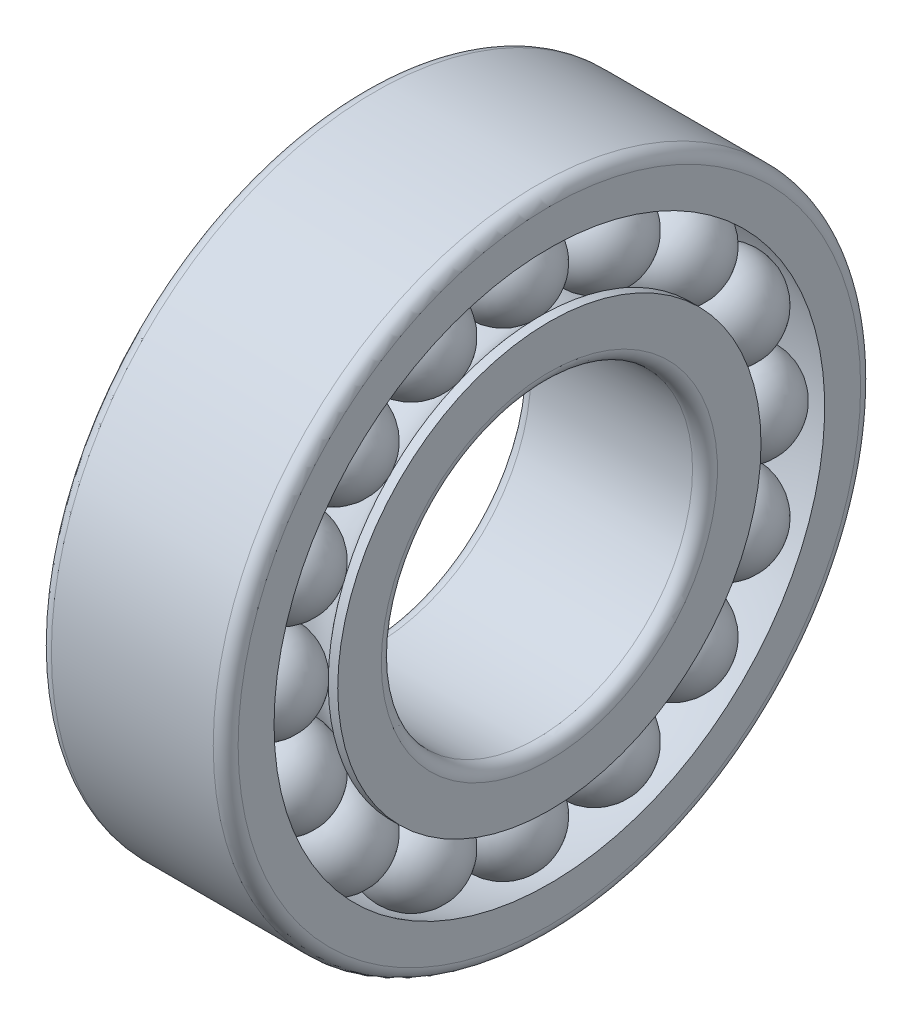
SolidWorks part; units mm, degrees
ref_plane "Front" through (0, 0, 0) normal (0, 0, 1) x (1, 0, 0)
ref_plane "Top" through (0, 0, 0) normal (0, 1, 0) x (1, 0, 0)
ref_plane "Right" through (0, 0, 0) normal (1, 0, 0) x (0, 0, -1)
sketch "Sketch1" plane through (0, 0, 0) normal (0, 0, 1) x (1, 0, 0)
  line L0 (0, 0) -> (10.4156, 0) construction
  line L1 (-7.5, 12.5) -> (7.5, 12.5)
  line L2 (7.5, 12.5) -> (7.5, 17)
  line L3 (7.5, 17) -> (6.7375, 17)
  line L4 (-7.5, 17) -> (-7.5, 12.5)
  line L5 (-6.7375, 17) -> (-7.5, 17)
  line L6 (0.7625, 17) -> (-0.7625, 17)
  circle A0 centre (-3.75, 19.25) radius 3.74 construction
  circle A1 centre (3.75, 19.25) radius 3.74 construction
  arc A2 (-6.7375, 17) -> (-0.7625, 17) centre (-3.75, 19.25) ccw
  arc A3 (0.7625, 17) -> (6.7375, 17) centre (3.75, 19.25) ccw
  point P8 (0, 12.5)
  dimension "QXD" = 7.48
  dimension "XD1" = 34
  dimension "XD" = 25
  dimension "DB" = 15
  dimension "QDD" = 38.5
  dimension "D1" = 3.75
  dimension "D2" = 3.75
revolve "Revovle1" add sketch "Sketch1" angle 360 about L0
sketch "Sketch2" plane through (0, 0, 0) normal (0, 0, 1) x (1, 0, 0)
  line L0 (-7.4995, 19.25) -> (-0.0005, 19.25)
  line L1 (-4.0336, 19.25) -> (6.5093, 19.25) construction
  arc A2 (-7.4995, 19.25) -> (-0.0005, 19.25) centre (-3.75, 19.25) ccw
  dimension "D2" = 3.75
  dimension "D1" = 19.25
  dimension "QXD" = 7.499
revolve "Revolve2" add sketch "Sketch2" angle 360 about L1
mirror "Mirror1" about plane through (0, 0, 0) normal (1, 0, 0) of "Revolve2"
sketch "Sketch3" plane through (0, 0, 0) normal (0, 0, 1) x (1, 0, 0)
  line L0 (-7.5, 22.1147) -> (-7.5, 26)
  line L1 (-7.5, 26) -> (7.5, 26)
  line L2 (7.5, 26) -> (7.5, 22.1147)
  line L5 (0, 0) -> (7.3928, 0) construction
  line L7 (7.5, -17) -> (7.5, 17) construction
  line L8 (-7.5, 17) -> (-7.5, -17) construction
  circle A0 centre (-3.75, 19.25) radius 3.74 construction
  circle A1 centre (3.75, 19.25) radius 3.74 construction
  arc A2 (7.5, 22.1147) -> (-7.5, 22.1147) centre (0, 0) ccw
  dimension "D2" = 7.48
  dimension "DD" = 52
  dimension "D1" = 19.25
  dimension "D3" = 3.75
  dimension "D4" = 3.75
revolve "Revolve3" add sketch "Sketch3" angle 360 about L5
pattern_circular "Circular-Pattern1" count 16 over 360 about axis through (0, 0, 0) along (1, 0, 0) of "Revolve2", "Mirror1"
fillet "Fillet1" radius 1 4 edges at (-7.5, 0, 12.5) (-7.5, 0, 26) (7.5, 0, 12.5) (7.5, 0, 26)
equation "\"XD1@Sketch1\" = \"XD@Sketch1\" +  ( \"DD@Sketch3\" - \"XD@Sketch1\" )  / 3"
equation "\"QDD@Sketch1\" = \"XD@Sketch1\" +  ( \"DD@Sketch3\" - \"XD@Sketch1\" )  / 2"
equation "\"QXD@Sketch1\" = \"DB@Sketch1\" / 2 - 0.02"
equation "\"D1@Sketch1\" = \"DB@Sketch1\" / 4"
equation "\"D2@Sketch1\" = \"D1@Sketch1\""
equation "\"QXD@Sketch2\" = \"DB@Sketch1\"/2-0.001"
equation "\"D2@Sketch2\" = \"D2@Sketch1\""
equation "\"D1@Sketch2\" = \"QDD@Sketch1\" / 2"
equation "\"D1@Sketch3\" = \"QDD@Sketch1\" / 2"
equation "\"D2@Sketch3\" = \"QXD@Sketch1\""
equation "\"D3@Sketch3\" = \"D2@Sketch1\""
equation "\"D4@Sketch3\" = \"D3@Sketch3\""
equation "\"D1@Circular-Pattern1\" = int( 3.14159265 / atn(( \"QXD@Sketch2\" / 2) / sqr(\"QDD@Sketch1\" *\"QDD@Sketch1\"/4 - ( \"QXD@Sketch2\" / 2) *  ( \"QXD@Sketch2\" / 2))))"
